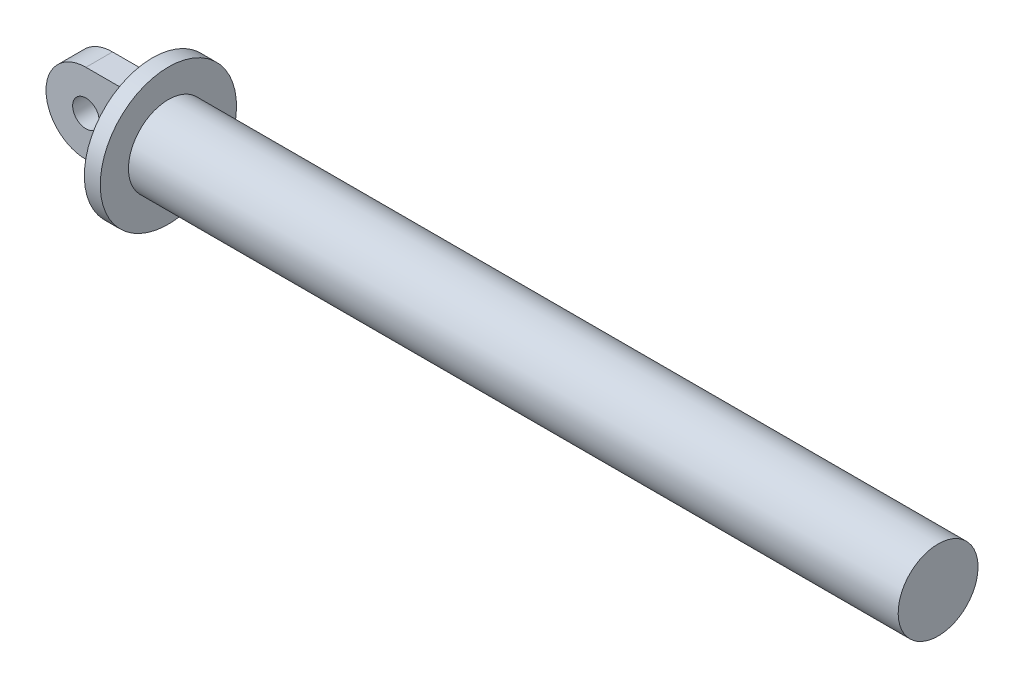
SolidWorks part; units mm, degrees
ref_plane "Front Plane" through (0, 0, 0) normal (0, 0, 1) x (1, 0, 0)
ref_plane "Top Plane" through (0, 0, 0) normal (0, 1, 0) x (1, 0, 0)
ref_plane "Right Plane" through (0, 0, 0) normal (1, 0, 0) x (0, 0, -1)
sketch "Sketch2" plane through (0, 0, 0) normal (0, 0, 1) x (1, 0, 0)
  line L1 (-25.9823, 28.402) -> (-5.9823, 28.402)
  line L3 (-25.9823, -1.598) -> (-5.9823, -1.598)
  line L4 (-5.9823, 28.402) -> (-5.9823, -1.598)
  circle A0 centre (-25.9823, 13.402) radius 5
  arc A1 (-25.9823, 28.402) -> (-25.9823, -1.598) centre (-25.9823, 13.402) ccw
  dimension "D1" = 10
  dimension "D2" = 30
  dimension "D3" = 20
extrude "Boss-Extrude1" add sketch "Sketch2" along normal mid plane 10
sketch "Sketch8" plane through (0, 0, 0) normal (0, 0, 1) x (1, 0, 0)
  line L0 (-5.9823, 28.402) -> (-5.9823, 39)
  line L1 (-5.9823, -1.598) -> (-5.9823, 28.402) construction
  line L2 (-5.9823, 28.402) -> (-25.9823, 28.402) construction
  line L3 (-5.9823, 39) -> (0, 39)
  line L4 (0, 39) -> (0, 28.402)
  line L5 (0, 28.402) -> (289.2157, 28.402)
  line L6 (289.2157, 28.402) -> (289.2157, 13.402)
  line L7 (289.2157, 13.402) -> (-5.9823, 13.402)
  line L8 (-5.9823, 13.402) -> (-5.9823, 28.402)
revolve "Revolve1" add sketch "Sketch8" angle 360 about L7
